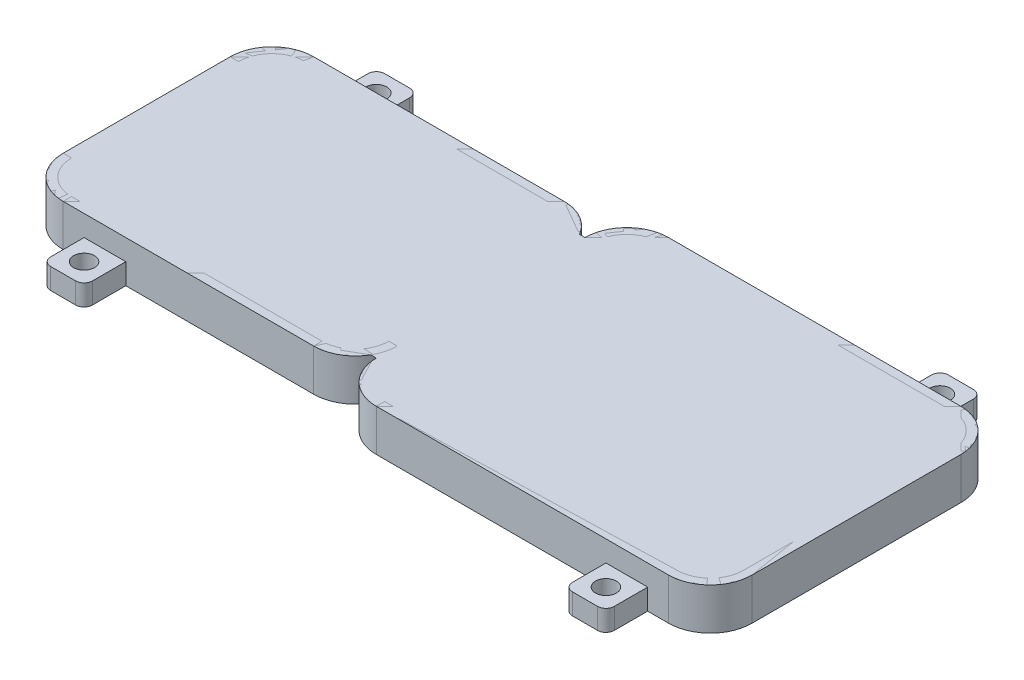
SolidWorks part; units mm, degrees
ref_plane "Front Plane" through (0, 0, 0) normal (0, 0, 1) x (1, 0, 0)
ref_plane "Top Plane" through (0, 0, 0) normal (0, 1, 0) x (1, 0, 0)
ref_plane "Right Plane" through (0, 0, 0) normal (1, 0, 0) x (0, 0, -1)
sketch "Sketch1" plane through (0, 0, 0) normal (0, 1, 0) x (1, 0, 0)
  line L1 (35, -35) -> (-35, -35)
  line L2 (45, -25) -> (45, 25)
  line L3 (35, 35) -> (-35, 35)
  line L4 (-45, -25) -> (-45, -20)
  line L5 (45, -35) -> (-45, 35) construction
  line L6 (45, 35) -> (-45, -35) construction
  line L11 (-55, 30) -> (-115, 30)
  line L13 (-55, -30) -> (-115, -30)
  line L14 (-125, 20) -> (-125, -20)
  line L15 (-55, -28) -> (-115, -28)
  line L16 (-123, 20) -> (-123, -20)
  line L17 (-55, 28) -> (-115, 28)
  line L18 (43, -25) -> (43, 25)
  line L19 (35, 33) -> (-35, 33)
  line L21 (35, -33) -> (-35, -33)
  line L22 (-47, 20) -> (-47, -20) construction
  line L23 (-45, 20) -> (-45, 25)
  line L24 (-47, -20) -> (-45, -20)
  line L25 (-45, -25) -> (-45, 25) construction
  line L26 (-45, 20) -> (-45, -20) construction
  line L27 (-43, -25) -> (-43, 25) construction
  line L28 (-47, 20) -> (-45, 20)
  line L29 (-43, -25) -> (-45, -20)
  line L30 (-45, 20) -> (-43, 25)
  arc A0 (-115, -30) -> (-125, -20) centre (-115, -20) cw
  arc A1 (-115, 30) -> (-125, 20) centre (-115, 20) ccw
  arc A2 (45, 25) -> (35, 35) centre (35, 25) ccw
  arc A3 (35, -35) -> (45, -25) centre (35, -25) ccw
  arc A4 (-35, 35) -> (-45, 25) centre (-35, 25) ccw
  arc A5 (-35, -35) -> (-45, -25) centre (-35, -25) cw
  arc A6 (-55, 30) -> (-45, 20) centre (-55, 20) cw
  arc A7 (-45, -20) -> (-55, -30) centre (-55, -20) cw
  arc A8 (-47, -20) -> (-55, -28) centre (-55, -20) cw
  arc A9 (-115, -28) -> (-123, -20) centre (-115, -20) cw
  arc A10 (-115, 28) -> (-123, 20) centre (-115, 20) ccw
  arc A11 (-55, 28) -> (-47, 20) centre (-55, 20) cw
  arc A12 (43, 25) -> (35, 33) centre (35, 25) ccw
  arc A13 (-35, 33) -> (-43, 25) centre (-35, 25) ccw
  arc A14 (-35, -33) -> (-43, -25) centre (-35, -25) cw
  arc A15 (35, -33) -> (43, -25) centre (35, -25) ccw
  point P0 (0, 0)
  point P14 (-125, -30)
  point P17 (-125, 30)
  point P32 (-45, 30)
  dimension "D5" = 10
  dimension "D1" = 70
  dimension "D2" = 90
  dimension "D3" = 80
  dimension "D4" = 60
  dimension "D6" = 2
  dimension "D7" = 2
extrude "Boss-Extrude1" add sketch "Sketch1" along normal blind 10 contours L17 A11 L28 A6 L11 A1 L14 A0 L13 A7 L24 A8 L15 A9 L16 A10 | A15 L21 A14 L29 L4 A5 L1 A3 L2 A2 L3 A4 L23 L30 A13 L19 A12 L18
sketch "Sketch2" plane through (0, 10, 0) normal (0, 1, 0) x (1, 0, 0)
  line L0 (-45, 25) -> (-46.3397, 25)
  line L1 (-45, -25) -> (-46.3397, -25)
  line L8 (-115, 28) -> (-55, 28)
  line L9 (-47, 20) -> (-45, 20)
  line L10 (-55, 30) -> (-115, 30)
  line L11 (-125, 20) -> (-125, -20)
  line L12 (-115, -30) -> (-55, -30)
  line L13 (-45, -20) -> (-47, -20)
  line L14 (-55, -28) -> (-115, -28)
  line L15 (-123, -20) -> (-123, 20)
  line L18 (-55, 30) -> (-115, 30)
  line L19 (-125, 20) -> (-125, -20)
  line L20 (-115, -30) -> (-55, -30)
  line L26 (35, -33) -> (-35, -33)
  line L27 (-43, -25) -> (-45, -20)
  line L28 (-45, -20) -> (-45, -25)
  line L29 (-35, -35) -> (35, -35)
  line L30 (45, -25) -> (45, 25)
  line L31 (35, 35) -> (-35, 35)
  line L32 (-45, 25) -> (-45, 20)
  line L33 (-45, 20) -> (-43, 25)
  line L34 (-35, 33) -> (35, 33)
  line L35 (43, 25) -> (43, -25)
  line L39 (-35, -35) -> (35, -35)
  line L40 (45, -25) -> (45, 25)
  line L41 (35, 35) -> (-35, 35)
  arc A8 (-47, 20) -> (-55, 28) centre (-55, 20) ccw
  arc A9 (-45, 20) -> (-55, 30) centre (-55, 20) ccw
  arc A10 (-115, 30) -> (-125, 20) centre (-115, 20) ccw
  arc A11 (-125, -20) -> (-115, -30) centre (-115, -20) ccw
  arc A12 (-55, -30) -> (-45, -20) centre (-55, -20) ccw
  arc A13 (-55, -28) -> (-47, -20) centre (-55, -20) ccw
  arc A14 (-123, -20) -> (-115, -28) centre (-115, -20) ccw
  arc A15 (-115, 28) -> (-123, 20) centre (-115, 20) ccw
  arc A17 (-46.3397, 25) -> (-55, 30) centre (-55, 20) ccw
  arc A18 (-115, 30) -> (-125, 20) centre (-115, 20) ccw
  arc A19 (-125, -20) -> (-115, -30) centre (-115, -20) ccw
  arc A20 (-55, -30) -> (-46.3397, -25) centre (-55, -20) ccw
  arc A24 (35, -33) -> (43, -25) centre (35, -25) ccw
  arc A25 (-43, -25) -> (-35, -33) centre (-35, -25) ccw
  arc A26 (-45, -25) -> (-35, -35) centre (-35, -25) ccw
  arc A27 (35, -35) -> (45, -25) centre (35, -25) ccw
  arc A28 (45, 25) -> (35, 35) centre (35, 25) ccw
  arc A29 (-35, 35) -> (-45, 25) centre (-35, 25) ccw
  arc A30 (-35, 33) -> (-43, 25) centre (-35, 25) ccw
  arc A31 (43, 25) -> (35, 33) centre (35, 25) ccw
  arc A34 (-45, -25) -> (-35, -35) centre (-35, -25) ccw
  arc A35 (35, -35) -> (45, -25) centre (35, -25) ccw
  arc A36 (45, 25) -> (35, 35) centre (35, 25) ccw
  arc A37 (-35, 35) -> (-45, 25) centre (-35, 25) ccw
  dimension "D1" = 0
  dimension "D2" = 0
surface "Surface-Plane1" sketch "Sketch2"
sketch "Sketch3" plane through (0, 0, 30) normal (0, 0, 1) x (1, 0, 0)
  line L0 (-55, 0) -> (-115, 0) construction
  line L1 (-110, 0) -> (-100, 0)
  line L2 (-110, 0) -> (-110, 5)
  line L3 (-110, 5) -> (-100, 5)
  line L4 (-100, 0) -> (-100, 5)
  line L5 (-115, 10) -> (-115, 0) construction
  dimension "D1" = 5
  dimension "D2" = 10
  dimension "D3" = 5
extrude "Boss-Extrude8" add sketch "Sketch3" along normal blind 10
sketch "Sketch4" plane through (0, 5, 0) normal (0, 1, 0) x (1, 0, 0)
  line L0 (-110, -35) -> (-100, -35) construction
  line L1 (-110, -40) -> (-110, -30) construction
  line L2 (-100, -40) -> (-100, -30) construction
  line L3 (-105, -30) -> (-105, -40) construction
  line L4 (-100, -30) -> (-110, -30) construction
  line L5 (-100, -40) -> (-110, -40) construction
  circle A0 centre (-105, -35) radius 2.5
  dimension "D1" = 5
extrude "Cut-Extrude1" cut sketch "Sketch4" against normal blind 10
fillet "Fillet1" radius 2 2 edges at (-100, 2.5, 40) (-110, 2.5, 40)
mirror "Mirror4" about plane through (0, 0, 0) normal (0, 0, 1) of "Fillet1", "Cut-Extrude1", "Boss-Extrude8"
ref_plane "Plane1" through (-45, 0, 0) normal (1, 0, 0) x (0, 0, -1)
sketch "Sketch5" plane through (0, 0, 35) normal (0, 0, 1) x (1, 0, 0)
  line L0 (35, 0) -> (-35, 0) construction
  line L1 (30, 0) -> (20, 0)
  line L2 (30, 0) -> (30, 5)
  line L3 (30, 5) -> (20, 5)
  line L4 (20, 0) -> (20, 5)
  line L5 (35, 10) -> (35, 0) construction
  dimension "D1" = 5
  dimension "D2" = 5
  dimension "D3" = 10
extrude "Boss-Extrude9" add sketch "Sketch5" along normal blind 10
sketch "Sketch7" plane through (0, 5, 0) normal (0, 1, 0) x (1, 0, 0)
  line L0 (20, -40) -> (30, -40) construction
  line L1 (20, -45) -> (20, -35) construction
  line L2 (30, -45) -> (30, -35) construction
  line L3 (25, -35) -> (25, -45) construction
  line L4 (30, -35) -> (20, -35) construction
  line L5 (30, -45) -> (20, -45) construction
  circle A0 centre (25, -40) radius 2.5
  dimension "D1" = 5
extrude "Cut-Extrude2" cut sketch "Sketch7" against normal blind 10
fillet "Fillet3" radius 2 2 edges at (30, 2.5, 45) (20, 2.5, 45)
mirror "Mirror18" about plane through (0, 0, 0) normal (0, 0, 1) of "Boss-Extrude9", "Cut-Extrude2", "Fillet3"
